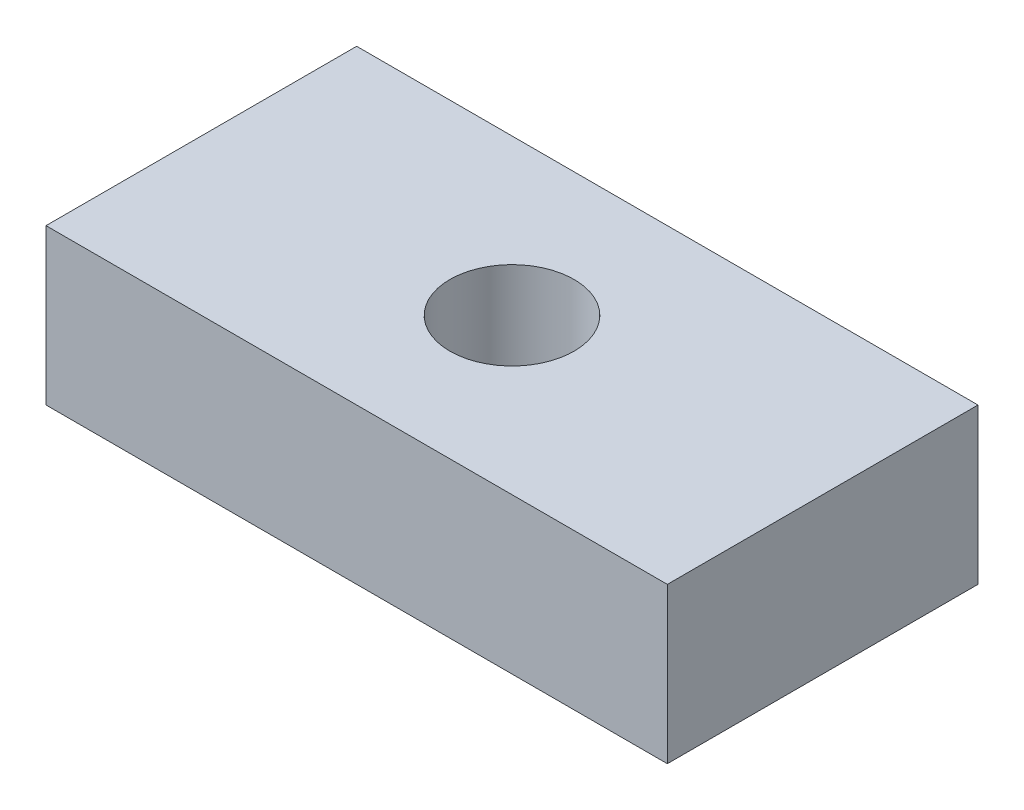
SolidWorks part; units mm, degrees
ref_plane "Front Plane" through (0, 0, 0) normal (0, 0, 1) x (1, 0, 0)
ref_plane "Top Plane" through (0, 0, 0) normal (0, 1, 0) x (1, 0, 0)
ref_plane "Right Plane" through (0, 0, 0) normal (1, 0, 0) x (0, 0, -1)
sketch "Sketch2" plane through (0, 0, 0) normal (0, 1, 0) x (1, 0, 0)
  line L1 (-36.3307, -13.4638) -> (3.6693, -13.4638)
  line L2 (-36.3307, -13.4638) -> (-36.3307, -33.4638)
  line L3 (-36.3307, -33.4638) -> (3.6693, -33.4638)
  line L4 (3.6693, -13.4638) -> (3.6693, -33.4638)
  dimension "D1" = 40
  dimension "D2" = 20
extrude "Boss-Extrude1" add sketch "Sketch2" along normal blind 10
sketch "Sketch3" plane through (0, 10, 0) normal (0, 1, 0) x (1, 0, 0)
  circle A0 centre (-16.3307, -23.4638) radius 4
extrude "Cut-Extrude1" cut sketch "Sketch3" against normal up to next
